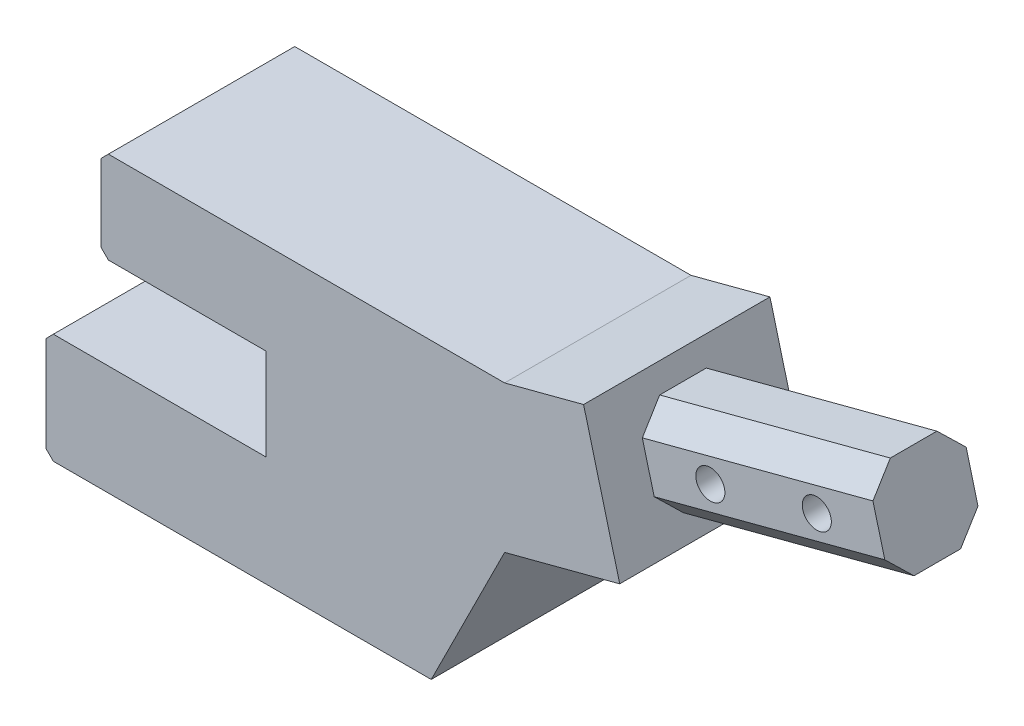
SolidWorks part; units mm, degrees
ref_plane "Alzado" through (0, 0, 0) normal (0, 0, 1) x (1, 0, 0)
ref_plane "Planta" through (0, 0, 0) normal (0, 1, 0) x (1, 0, 0)
ref_plane "Vista lateral" through (0, 0, 0) normal (1, 0, 0) x (0, 0, -1)
sketch "Croquis1" plane through (0, 0, 0) normal (0, 0, 1) x (1, 0, 0)
  line L0 (21.5228, 45.6639) -> (31.3674, 8.2546)
  line L1 (31.3674, 8.2546) -> (0, 0)
  line L2 (0, 0) -> (-20, -40)
  line L3 (-20, -40) -> (-123, -40)
  line L4 (-123, -40) -> (-125, -38.0129)
  line L5 (-125, -38.0129) -> (-125, -12.0129)
  line L6 (-125, -12.0129) -> (-123.0001, -10)
  line L7 (-123.0001, -10) -> (-65.0001, -10)
  line L8 (-65.0001, -10) -> (-65.0001, 15)
  line L9 (-65.0001, 15) -> (-107.9935, 15)
  line L10 (-107.9935, 15) -> (-110, 16.9935)
  line L11 (-110, 16.9935) -> (-110, 37.9935)
  line L12 (-110, 37.9935) -> (-108.0065, 40)
  line L13 (-108.0065, 40) -> (0, 40)
  line L14 (0, 40) -> (21.5228, 45.6639)
  point P15 (-125, -25.0129)
  point P16 (-110, 27.4935)
  dimension "D1" = 30
  dimension "D2" = 25
  dimension "D3" = 103
  dimension "D4" = 26
  dimension "D5" = 58
  dimension "D6" = 25
  dimension "D7" = 156.3674
  dimension "D8" = 146.5228
  dimension "D9" = 125
  dimension "D10" = 110
  dimension "D11" = 21
  dimension "D13" = 21.5228
  dimension "D14" = 38.683
  dimension "D15" = 20
  dimension "D17" = 48.2546
extrude "Saliente-Extruir1" add sketch "Croquis1" along normal mid plane 50.8
sketch "Croquis2" plane through (0, 0, 0) normal (0, 0, 1) x (1, 0, 0)
  line L5 (29.6772, 14.6774) -> (92.537, 31.2195)
  line L6 (31.3674, 8.2546) -> (21.5228, 45.6639) construction
  line L7 (92.537, 31.2195) -> (86.0728, 55.7832)
  line L8 (86.0728, 55.7832) -> (23.213, 39.2411)
  line L9 (23.213, 39.2411) -> (29.6772, 14.6774)
  point P7 (26.4451, 26.9592)
  point P8 (26.4451, 26.9592)
  dimension "D1" = 65
  dimension "D2" = 25.4
extrude "Saliente-Extruir2" add sketch "Croquis2" along normal mid plane 25.4
sketch "Croquis4" plane through (0, 0, 12.7) normal (0, 0, 1) x (1, 0, 0)
  line L0 (43.3689, 31.4129) -> (72.3811, 39.0477) construction
  line L1 (86.0728, 55.7832) -> (23.213, 39.2411) construction
  line L2 (54.6429, 47.5122) -> (57.875, 35.2303) construction
  line L3 (92.537, 31.2195) -> (86.0728, 55.7832) construction
  line L4 (43.3689, 31.4129) -> (26.4451, 26.9592) construction
  line L5 (23.213, 39.2411) -> (29.6772, 14.6774) construction
  circle A0 centre (72.3811, 39.0477) radius 3.9687
  circle A1 centre (43.3689, 31.4129) radius 3.9687
  point P8 (89.3049, 43.5014)
  dimension "D2" = 7.9375
  dimension "D1" = 30
extrude "Cortar-Extruir2" cut sketch "Croquis4" against normal through all
fillet "Redondeo1" radius 6.35 4 edges at (61.1071, 22.9485, -12.7) (61.1071, 22.9485, 12.7) (54.6429, 47.5122, -12.7) (54.6429, 47.5122, 12.7) profile chamfer
